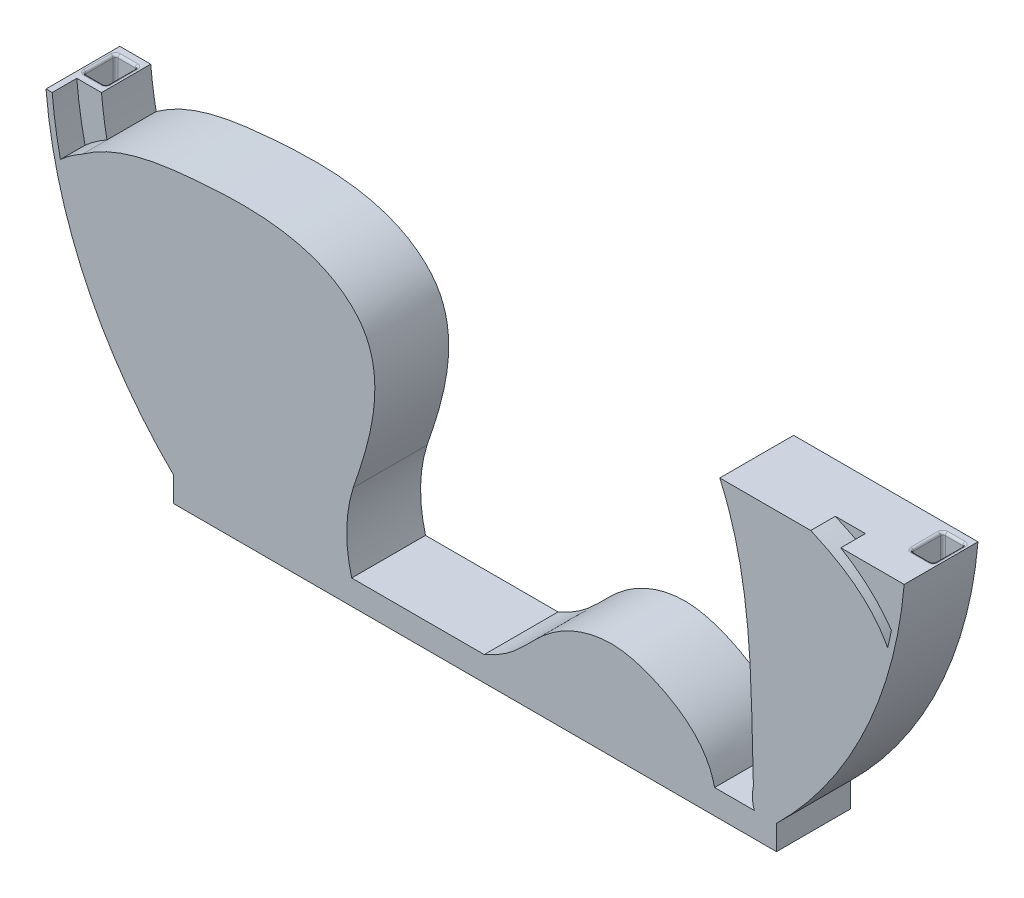
SolidWorks part; units mm, degrees
ref_plane "Front Plane" through (0, 0, 0) normal (0, 0, 1) x (1, 0, 0)
ref_plane "Top Plane" through (0, 0, 0) normal (0, 1, 0) x (1, 0, 0)
ref_plane "Right Plane" through (0, 0, 0) normal (1, 0, 0) x (0, 0, -1)
sketch "Sketch1" plane through (0, 0, 0) normal (0, 0, 1) x (1, 0, 0)
  line L0 (-471.0205, -57.4121) -> (528.9795, -57.4121) construction
sketch "Sketch2" plane through (0, 0, 0) normal (0, 0, 1) x (1, 0, 0)
  circle A0 centre (0, 0) radius 88.9
  arc A1 (-82.3152, -6.2211) -> (-81.0762, -15.5293) centre (0, 0) ccw
  arc A2 (37.7353, 73.4204) -> (24.5391, 78.8184) centre (0, 0) ccw
  arc A3 (49.8048, -65.833) -> (57.4511, -59.278) centre (0, 0) ccw
  spline S0 degree 3 poles (24.5391, 78.8184) (20.4556, 74.4117) (17.565, 65.825) (9.5129, 57.4487) (-6.2643, 43.842) (-22.0344, 67.8815) (-34.9463, 64.7741) knots 0 0 0 0 0.241589 0.34509 0.475626 1 1 1 1
  spline S1 degree 3 poles (-34.9463, 64.7741) (-40.5341, 56.6548) (-49.8264, 42.328) (-53.8975, 22.9229) (-55.1221, 8.6973) (-64.9776, -2.4901) (-73.6276, -8.8721) (-82.3152, -6.2211) knots 0 0 0 0 0.323422 0.539679 0.642017 0.776512 1 1 1 1
  spline S2 degree 3 poles (-81.0762, -15.5293) (-73.907, -10.3296) (-59.0461, -8.1934) (-41.1188, -7.6218) (-29.401, -11.3021) (-16.4021, -22.1309) (-22.5345, -39.5971) (-25.1747, -47.2363) knots 0 0 0 0 0.276571 0.483746 0.575309 0.672728 1 1 1 1
  spline S3 degree 2 poles (-25.1747, -47.2363) (-27.7826, -55.6887) (-25.2554, -64.2761) knots 0 0 0 1 1 1
  spline S4 degree 3 poles (-25.2554, -64.2761) (-19.569, -66.3264) (-8.1919, -67.1791) (6.6981, -62.4525) (13.7011, -53.6565) (20.9918, -49.375) (29.1491, -47.7149) (41.3216, -51.6056) (49.1187, -58.0567) (49.8048, -65.833) knots 0 0 0 0 0.203689 0.383929 0.501194 0.577509 0.667833 0.774874 1 1 1 1
  spline S5 degree 3 poles (57.4511, -59.278) (56.7569, -39.6924) (57.9372, -17.2532) (46.2956, 0) knots 0 0 0 0 1 1 1 1
  spline S6 degree 3 poles (46.2956, 0) (29.3524, 2.1608) (12.4769, -1.83) (-4.097, -4.8387) knots 0 0 0 0 1 1 1 1
  spline S7 degree 3 poles (-4.097, -4.8387) (-9.0033, -4.5386) (-9.1745, 2.8276) (-6.8237, 13.9795) (0.4609, 29.7843) (13.9721, 51.5725) (27.3945, 67.5356) (37.7353, 73.4204) knots 0 0 0 0 0.104628 0.200083 0.362714 0.636377 1 1 1 1
  dimension "D1" = 177.8
  dimension "D2" = 165.1
extrude "Boss-Extrude1" add sketch "Sketch2" along normal mid plane 15.24
ref_plane "Plane1" through (0, -7.62, 0) normal (0, 1, 0) x (1, 0, 0)
sketch "Sketch3" plane through (0, 0, 7.62) normal (0, 0, 1) x (1, 0, 0)
  arc A0 (45.0312, -76.6512) -> (59.2971, -66.2349) centre (0, 0) ccw
  circle A1 centre (0, 0) radius 88.9
  arc A2 (-88.6825, 6.2145) -> (-86.675, -19.7649) centre (0, 0) ccw
  arc A3 (46.2956, 75.8942) -> (29.9098, 83.7175) centre (0, 0) ccw
  arc A5 (49.8048, -65.833) -> (57.4511, -59.278) centre (0, 0) ccw
  arc A6 (-82.3152, -6.2211) -> (-81.0762, -15.5293) centre (0, 0) ccw
  arc A7 (37.7353, 73.4204) -> (24.5391, 78.8184) centre (0, 0) ccw
  arc A8 (49.8048, -65.833) -> (57.4511, -59.278) centre (0, 0) ccw
  arc A9 (-82.3152, -6.2211) -> (-81.0762, -15.5293) centre (0, 0) ccw
  arc A10 (37.7353, 73.4204) -> (24.5391, 78.8184) centre (0, 0) ccw
  parabola Q1 (-25.1747, -47.2363) -> (-25.2554, -64.2761) focus (-12.3697, -55.4847) apex (-26.4894, -55.1133)
  spline S0 degree 2 poles (24.5391, 78.8184) (26.688, 81.9029) (29.9098, 83.7175) knots 0 0 0 1 1 1
  spline S1 degree 2 poles (37.7353, 73.4204) (41.6923, 75.7816) (46.2956, 75.8942) knots 0 0 0 1 1 1
  spline S2 degree 2 poles (49.8048, -65.833) (50.2908, -72.1824) (45.0312, -76.6512) knots 0 0 0 1 1 1
  spline S3 degree 2 poles (57.4511, -59.278) (56.5901, -63.2228) (59.2971, -66.2349) knots 0 0 0 1 1 1
  spline S4 degree 2 poles (-82.3152, -6.2211) (-88.132, -1.4992) (-88.6825, 6.2145) knots 0 0 0 1 1 1
  spline S5 degree 2 poles (-81.0762, -15.5293) (-84.1856, -17.2384) (-86.675, -19.7649) knots 0 0 0 1 1 1
  spline S7 degree 3 poles (797.4031, 593.1493) (0.2989, -46.9604) (-12.291, -11.9571) (-6.8237, 13.9795) (0.4609, 29.7843) (48.148, 106.6846) (139.4225, 154.8359) (772.5047, -604.8924) knots -0.480865 -0.480865 -0.480865 -0.480865 0.104628 0.200083 0.362714 0.636377 3.023358 3.023358 3.023358 3.023358 only from (-4.097, -4.8387) to (37.7353, 73.4204)
  spline S8 degree 3 poles (252.9136, -978.4205) (116.1017, 1038.4288) (-125.7429, -1046.9057) (-203.2003, 975.1295) knots -4.374054 -4.374054 -4.374054 -4.374054 6.105359 6.105359 6.105359 6.105359 only from (46.2956, 0) to (-4.097, -4.8387)
  spline S9 degree 3 poles (990.0767, 301.5646) (-883.5718, -676.2898) (1013.4306, 526.4735) (-922.0419, -249.5528) knots -3.853706 -3.853706 -3.853706 -3.853706 4.174069 4.174069 4.174069 4.174069 only from (57.4511, -59.278) to (46.2956, 0)
  spline S10 degree 3 poles (287.5037, 885.5524) (-143.4767, 77.5467) (-70.7404, -87.034) (6.6981, -62.4525) (13.7011, -53.6565) (20.9918, -49.375) (29.1491, -47.7149) (73.6514, -61.9392) (81.5637, -140.3542) (-751.2392, -664.4206) knots -2.105379 -2.105379 -2.105379 -2.105379 0.203689 0.383929 0.501194 0.577509 0.667833 0.774874 2.12212 2.12212 2.12212 2.12212 only from (-25.2554, -64.2761) to (49.8048, -65.833)
  spline S11 degree 3 poles (118.7702, -995.3507) (-163.8661, -39.4174) (-105.7067, -9.6811) (-41.1188, -7.6218) (-29.401, -11.3021) (14.3806, -47.7745) (-197.2699, -211.0705) (662.1001, 679.1083) knots -1.497399 -1.497399 -1.497399 -1.497399 0.276571 0.483746 0.575309 0.672728 2.222535 2.222535 2.222535 2.222535 only from (-81.0762, -15.5293) to (-25.1747, -47.2363)
  spline S12 degree 3 poles (-1006.572, 301.2797) (188.103, 148.9815) (-33.2102, 121.5314) (-53.8975, 22.9229) (-55.1221, 8.6973) (-85.5018, -25.7879) (-127.0209, -26.4291) (-604.6871, 846.4702) knots -2.62044 -2.62044 -2.62044 -2.62044 0.323422 0.539679 0.642017 0.776512 1.958619 1.958619 1.958619 1.958619 only from (-34.9463, 64.7741) to (-82.3152, -6.2211)
  spline S13 degree 3 poles (862.9419, -466.2311) (-1.0647, 177.7851) (40.0673, 89.2334) (9.5129, 57.4487) (-32.0652, 21.5906) (-89.4617, 287.288) (-116.9144, -931.8483) knots -1.329179 -1.329179 -1.329179 -1.329179 0.241589 0.34509 0.475626 2.240257 2.240257 2.240257 2.240257 only from (24.5391, 78.8184) to (-34.9463, 64.7741)
  dimension "D1" = 0
  dimension "D2" = 0
extrude "Cut-Extrude1" cut sketch "Sketch3" against normal blind 5.08
sketch "Sketch4" plane through (0, 0, 7.62) normal (0, 0, 1) x (1, 0, 0)
  line L0 (-34.9463, 64.7741) -> (-35.0973, 62.4446)
  arc A0 (-64.8446, 60.8144) -> (-68.4378, 56.7404) centre (0, 0) ccw
  circle A1 centre (0, 0) radius 88.9
  arc A2 (0.6318, -88.8978) -> (4.2385, -88.7989) centre (0, 0) ccw
  arc A3 (86.0164, -22.4585) -> (86.9207, -18.6546) centre (0, 0) ccw
  arc A5 (49.8048, -65.833) -> (57.4511, -59.278) centre (0, 0) ccw
  arc A6 (-82.3152, -6.2211) -> (-81.0762, -15.5293) centre (0, 0) ccw
  arc A7 (37.7353, 73.4204) -> (24.5391, 78.8184) centre (0, 0) ccw
  parabola Q1 (-25.1747, -47.2363) -> (-25.2554, -64.2761) focus (-12.3697, -55.4847) apex (-26.4894, -55.1133)
  spline S0 degree 2 poles (-34.9463, 64.7741) (-50.3518, 67.3824) (-64.8446, 60.8144) knots 0 0 0 1 1 1
  spline S1 degree 2 poles (-35.0973, 62.4446) (-52.4249, 65.6078) (-68.4378, 56.7404) knots 0 0 0 1 1 1
  spline S2 degree 3 poles (46.2956, 0) (53.1383, -0.1215) (68.5609, -2.5532) (82.3308, -11.0602) (86.9207, -18.6546) knots 0 0 0 0 0.442007 1 1 1 1
  spline S3 degree 3 poles (47.9006, -2.5461) (54.1052, -2.3836) (68.546, -6.4117) (82.2788, -13.6612) (86.0164, -22.4585) knots 0 0 0 0 0.409341 1 1 1 1
  spline S4 degree 3 poles (-25.2554, -64.2761) (-21.1278, -75.8582) (-10.4674, -84.3936) (0.6318, -88.8978) knots 0 0 0 0 1 1 1 1
  spline S5 degree 3 poles (-22.4522, -65.1518) (-17.4352, -76.2865) (-6.0163, -83.0979) (4.2385, -88.7989) knots 0 0 0 0 1 1 1 1
  spline S7 degree 3 poles (797.4031, 593.1493) (0.2989, -46.9604) (-12.291, -11.9571) (-6.8237, 13.9795) (0.4609, 29.7843) (48.148, 106.6846) (139.4225, 154.8359) (772.5047, -604.8924) knots -0.480865 -0.480865 -0.480865 -0.480865 0.104628 0.200083 0.362714 0.636377 3.023358 3.023358 3.023358 3.023358 only from (-4.097, -4.8387) to (37.7353, 73.4204)
  spline S8 degree 3 poles (252.9136, -978.4205) (116.1017, 1038.4288) (-125.7429, -1046.9057) (-203.2003, 975.1295) knots -4.374054 -4.374054 -4.374054 -4.374054 6.105359 6.105359 6.105359 6.105359 only from (46.2956, 0) to (-4.097, -4.8387)
  spline S9 degree 3 poles (2750.4497, 1250.492) (-2664.0011, -1715.2033) (2817.268, 1518.6416) (-2752.7289, -1054.4103) knots -5.547082 -5.547082 -5.547082 -5.547082 5.883178 5.883178 5.883178 5.883178 only from (57.4511, -59.278) to (46.2956, 0)
  spline S10 degree 3 poles (1330.581, 2591.3174) (-209.0004, 264.8137) (-104.1775, -97.6481) (6.6981, -62.4525) (13.7011, -53.6565) (20.9918, -49.375) (29.1491, -47.7149) (91.1887, -67.5447) (82.2329, -217.3865) (-2469.3122, -1687.681) knots -3.230872 -3.230872 -3.230872 -3.230872 0.203689 0.383929 0.501194 0.577509 0.667833 0.774874 2.730813 2.730813 2.730813 2.730813 only from (-25.2554, -64.2761) to (49.8048, -65.833)
  spline S11 degree 3 poles (118.7702, -995.3507) (-163.8661, -39.4174) (-105.7067, -9.6811) (-41.1188, -7.6218) (-29.401, -11.3021) (14.3806, -47.7745) (-197.2699, -211.0705) (662.1001, 679.1083) knots -1.497399 -1.497399 -1.497399 -1.497399 0.276571 0.483746 0.575309 0.672728 2.222535 2.222535 2.222535 2.222535 only from (-81.0762, -15.5293) to (-25.1747, -47.2363)
  spline S12 degree 3 poles (-2993.0961, 532.3769) (364.9707, 159.8233) (-26.2899, 154.5178) (-53.8975, 22.9229) (-55.1221, 8.6973) (-96.7925, -38.6043) (-162.4194, -21.9121) (-1545.0332, 2611.4959) knots -3.711795 -3.711795 -3.711795 -3.711795 0.323422 0.539679 0.642017 0.776512 2.485967 2.485967 2.485967 2.485967 only from (-34.9463, 64.7741) to (-82.3152, -6.2211)
  spline S13 degree 3 poles (862.9419, -466.2311) (-1.0647, 177.7851) (40.0673, 89.2334) (9.5129, 57.4487) (-32.0652, 21.5906) (-89.4617, 287.288) (-116.9144, -931.8483) knots -1.329179 -1.329179 -1.329179 -1.329179 0.241589 0.34509 0.475626 2.240257 2.240257 2.240257 2.240257 only from (24.5391, 78.8184) to (-34.9463, 64.7741)
  spline S16 degree 3 poles (47.9006, -2.5461) (47.3947, -1.6858) (46.8602, -0.8368) (46.2956, 0) knots 0.951499 0.951499 0.951499 0.951499 1 1 1 1
  spline S17 degree 3 poles (-25.2554, -64.2761) (-24.3298, -64.6099) (-23.3949, -64.9013) (-22.4522, -65.1518) knots 0 0 0 0 0.033156 0.033156 0.033156 0.033156
  spline S19 degree 3 poles (-34.9463, 64.7741) (-35.4279, 64.0742) (-35.9094, 63.371) (-36.3894, 62.664) knots 0 0 0 0 0.027876 0.027876 0.027876 0.027876
  dimension "D1" = 0
  dimension "D2" = 0
extrude "Cut-Extrude2" cut sketch "Sketch4" against normal blind 5.08 contours S16 S3 A3 S2 | S17 S4 A2 S5 | S0 A0 S1 L0
sketch "Sketch5" plane through (0, -7.62, 0) normal (0, 1, 0) x (1, 0, 0)
  line L1 (-223.9278, 48.3173) -> (223.9278, 48.3173)
  line L2 (-223.9278, 48.3173) -> (-223.9278, -48.3173)
  line L3 (-223.9278, -48.3173) -> (223.9278, -48.3173)
  line L4 (223.9278, 48.3173) -> (223.9278, -48.3173)
  line L5 (-223.9278, 48.3173) -> (223.9278, -48.3173) construction
  line L6 (-223.9278, -48.3173) -> (223.9278, 48.3173) construction
  point P0 (0, 0)
sketch "Sketch6" plane through (0, 0, 0) normal (0, 0, 1) x (1, 0, 0)
  circle A0 centre (0, 0) radius 88.9
  circle A1 centre (0, 0) radius 87.63
  dimension "D1" = 177.8
  dimension "D2" = 175.26
extrude "Boss-Extrude2" add sketch "Sketch6" along normal mid plane 15.24
extrude "Cut-Extrude3" cut sketch "Sketch5" along normal through all
sketch "Sketch7" plane through (0, -7.62, 0) normal (0, 1, 0) x (1, 0, 0)
  line L0 (-82.1976, 7.62) -> (-88.5728, 7.62) construction
  line L1 (-87.1632, 5.842) -> (-83.6072, 5.842)
  line L2 (-87.6712, 5.334) -> (-87.6712, -0.254)
  line L3 (-87.1632, -0.762) -> (-83.6072, -0.762)
  line L4 (-83.0992, 5.334) -> (-83.0992, -0.254)
  line L5 (-87.6712, 5.842) -> (-83.0992, -0.762) construction
  line L6 (-87.6712, -0.762) -> (-83.0992, 5.842) construction
  line L7 (-82.1976, 7.62) -> (-82.1976, -2.54) construction
  line L8 (0, 0) -> (0, 15.9016) construction
  line L9 (87.1632, -0.762) -> (83.6072, -0.762)
  line L10 (83.0992, 5.334) -> (83.0992, -0.254)
  line L11 (87.1632, 5.842) -> (83.6072, 5.842)
  line L12 (87.6712, 5.334) -> (87.6712, -0.254)
  arc A0 (-87.6712, -0.254) -> (-87.1632, -0.762) centre (-87.1632, -0.254) ccw
  arc A1 (-83.6072, -0.762) -> (-83.0992, -0.254) centre (-83.6072, -0.254) ccw
  arc A2 (-83.6072, 5.842) -> (-83.0992, 5.334) centre (-83.6072, 5.334) cw
  arc A3 (-87.1632, 5.842) -> (-87.6712, 5.334) centre (-87.1632, 5.334) ccw
  arc A4 (83.6072, -0.762) -> (83.0992, -0.254) centre (83.6072, -0.254) cw
  arc A5 (83.6072, 5.842) -> (83.0992, 5.334) centre (83.6072, 5.334) ccw
  arc A6 (87.6712, -0.254) -> (87.1632, -0.762) centre (87.1632, -0.254) cw
  arc A7 (87.1632, 5.842) -> (87.6712, 5.334) centre (87.1632, 5.334) cw
  point P0 (-85.3852, 2.54)
  point P7 (-85.3852, 7.62)
  point P8 (-85.3852, 5.842)
  point P11 (-82.1976, 2.54)
  point P12 (-83.0992, 2.54)
  dimension "D3" = 0.508
  dimension "D1" = 4.572
  dimension "D2" = 6.604
extrude "Cut-Extrude4" cut sketch "Sketch7" against normal blind 5.08
fillet "Fillet1" radius 0.508 8 edges at (-83.248, -7.62, -5.6932) (-83.0992, -7.62, -2.54) (-83.248, -7.62, 0.6132) (-85.3852, -7.62, 0.762) (-87.5224, -7.62, 0.6132) (-87.6712, -7.62, -2.54) (-87.5224, -7.62, -5.6932) (-85.3852, -7.62, -5.842)
fillet "Fillet2" radius 0.508 8 edges at (87.5224, -7.62, -5.6932) (87.6712, -7.62, -2.54) (87.5224, -7.62, 0.6132) (85.3852, -7.62, 0.762) (83.248, -7.62, 0.6132) (83.0992, -7.62, -2.54) (83.248, -7.62, -5.6932) (85.3852, -7.62, -5.842)
ref_plane "Plane2" through (0, -63.5, 0) normal (0, -1, 0) x (-1, 0, 0)
sketch "Sketch8" plane through (0, -63.5, 0) normal (0, -1, 0) x (-1, 0, 0)
  line L1 (-105.0372, 27.1715) -> (130.4325, 27.1715)
  line L2 (-105.0372, 27.1715) -> (-105.0372, -35.8513)
  line L3 (-105.0372, -35.8513) -> (130.4325, -35.8513)
  line L4 (130.4325, 27.1715) -> (130.4325, -35.8513)
extrude "Cut-Extrude6" cut sketch "Sketch8" along normal blind 30.48
sketch "Sketch11" plane through (0, -63.5, 0) normal (0, -1, 0) x (-1, 0, 0)
  line L1 (-62.217, 7.62) -> (62.217, 7.62)
  line L2 (-62.217, 7.62) -> (-62.217, -7.62)
  line L3 (-62.217, -7.62) -> (62.217, -7.62)
  line L4 (62.217, 7.62) -> (62.217, -7.62)
extrude "Boss-Extrude3" add sketch "Sketch11" along normal blind 5.08
sketch "Sketch12" plane through (0, -68.58, 0) normal (0, -1, 0) x (1, 0, 0)
  line L1 (-4.318, 2.54) -> (4.318, 2.54)
  line L2 (-5.08, 1.778) -> (-5.08, -1.778)
  line L3 (-4.318, -2.54) -> (4.318, -2.54)
  line L4 (5.08, 1.778) -> (5.08, -1.778)
  line L5 (-5.08, 2.54) -> (5.08, -2.54) construction
  line L6 (-5.08, -2.54) -> (5.08, 2.54) construction
  arc A0 (4.318, 2.54) -> (5.08, 1.778) centre (4.318, 1.778) cw
  arc A1 (-5.08, -1.778) -> (-4.318, -2.54) centre (-4.318, -1.778) ccw
  arc A2 (4.318, -2.54) -> (5.08, -1.778) centre (4.318, -1.778) ccw
  arc A3 (-4.318, 2.54) -> (-5.08, 1.778) centre (-4.318, 1.778) ccw
  point P0 (0, 0)
  dimension "D3" = 0.762
  dimension "D1" = 10.16
  dimension "D2" = 5.08
extrude "Boss-Extrude4" add sketch "Sketch12" along normal blind 5.08
